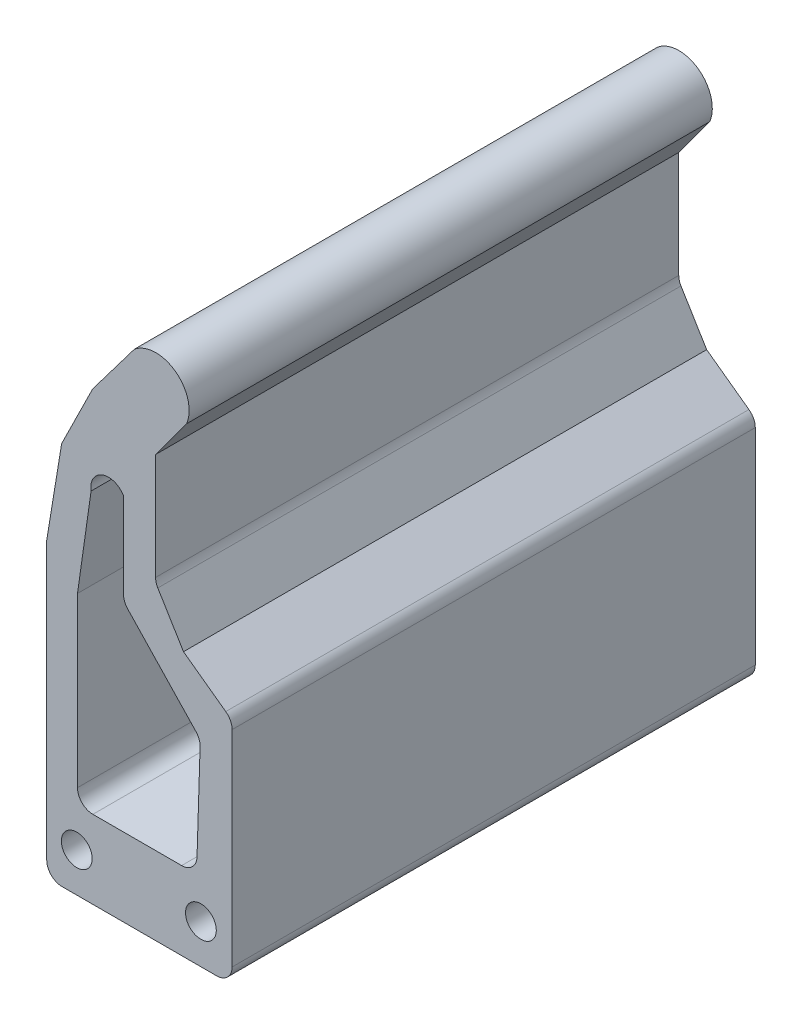
SolidWorks part; units mm, degrees
ref_plane "Front Plane" through (0, 0, 0) normal (0, 0, 1) x (1, 0, 0)
ref_plane "Top Plane" through (0, 0, 0) normal (0, 1, 0) x (1, 0, 0)
ref_plane "Right Plane" through (0, 0, 0) normal (1, 0, 0) x (0, 0, -1)
other "Graphic1"
ref_plane "Plane1" through (0, 0, 40) normal (0, 0, 1) x (1, 0, 0)
sketch "Sketch1" plane through (0, 0, 40) normal (0, 0, 1) x (1, 0, 0)
  line L0 (-300, 367) -> (-300, 348)
  line L1 (-300, 348) -> (-287.9516, 348)
  line L2 (-287.9516, 348) -> (-287.9516, 362.8718)
  line L3 (-287.9516, 362.8718) -> (-291.1109, 365.1664)
  line L4 (-291.1109, 365.1664) -> (-292.9258, 368.1591)
  line L5 (-292.9258, 368.1591) -> (-292.9258, 375.3591)
  line L6 (-292.9258, 375.3591) -> (-290.9105, 378.0975)
  line L7 (-300, 367) -> (-299.0296, 372.921)
  line L8 (-299.0296, 372.921) -> (-297.0124, 377.0093)
  line L9 (-297.0124, 377.0093) -> (-294.3, 380.6)
  arc A0 (-294.3, 380.6) -> (-290.9105, 378.0975) centre (-292.9147, 378.9296) cw
extrude "Boss-Extrude1" add sketch "Sketch1" along normal blind 34
sketch "Sketch2" plane through (0, 0, 74) normal (0, 0, 1) x (1, 0, 0)
  line L0 (-297.1166, 371.2077) -> (-298, 365)
  line L1 (-298, 365) -> (-298, 353.0704)
  line L2 (-298, 353.0704) -> (-290.2634, 353.0704)
  line L3 (-290.2634, 353.0704) -> (-290.0188, 360.779)
  line L4 (-290.0188, 360.779) -> (-295.01, 366.0466)
  line L5 (-295.01, 366.0466) -> (-295.01, 371.9952)
  arc A0 (-297.1166, 371.2077) -> (-295.01, 371.9952) centre (-295.9914, 371.409) cw
extrude "Cut-Extrude1" cut sketch "Sketch2" against normal blind 32
sketch "Sketch3" plane through (0, 0, 74) normal (0, 0, 1) x (1, 0, 0)
  circle A0 centre (-298.0464, 350.5461) radius 1
  circle A1 centre (-289.9795, 350.5461) radius 1
extrude "Cut-Extrude2" cut sketch "Sketch3" against normal blind 32
fillet "Fillet2" radius 1 8 edges at (-292.9258, 368.1591, 57) (-287.9516, 362.8718, 57) (-287.9516, 348, 57) (-300, 348, 57) (-290.0188, 360.779, 58) (-295.01, 366.0466, 58) (-290.2634, 353.0704, 58) (-298, 353.0704, 58)
